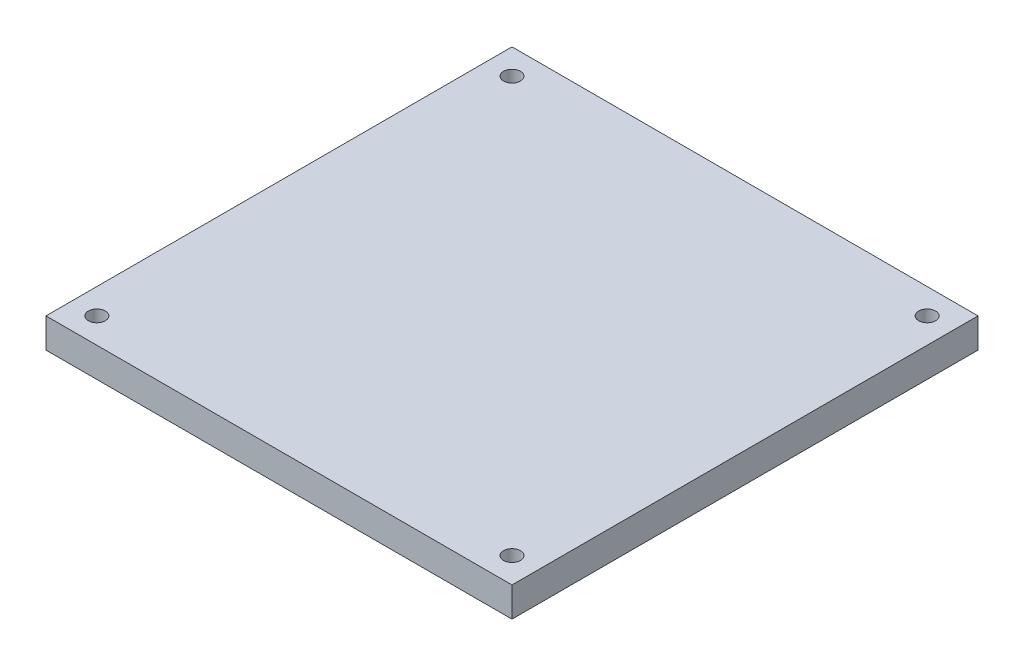
SolidWorks part; units mm, degrees
ref_plane "Plan de face" through (0, 0, 0) normal (0, 0, 1) x (1, 0, 0)
ref_plane "Plan de dessus" through (0, 0, 0) normal (0, 1, 0) x (1, 0, 0)
ref_plane "Plan de droite" through (0, 0, 0) normal (1, 0, 0) x (0, 0, -1)
sketch "Esquisse1" plane through (0, 0, 0) normal (0, 1, 0) x (1, 0, 0)
  line L0 (-26.5217, 31.7252) -> (-26.5217, -78.2748)
  line L1 (-26.5217, -78.2748) -> (83.4783, -78.2748)
  line L2 (83.4783, -78.2748) -> (83.4783, 31.7252)
  line L3 (83.4783, 31.7252) -> (-26.5217, 31.7252)
  dimension "D1" = 110
  dimension "D2" = 110
extrude "Boss.-Extru.1" add sketch "Esquisse1" along normal blind 7
sketch "Esquisse4" plane through (0, 7, 0) normal (0, 1, 0) x (1, 0, 0)
  line L0 (-26.5217, 31.7252) -> (-26.5217, -78.2748) construction
  line L1 (-26.5217, -78.2748) -> (83.4783, -78.2748) construction
  line L2 (83.4783, 31.7252) -> (-26.5217, 31.7252) construction
  line L3 (83.4783, -78.2748) -> (83.4783, 31.7252) construction
  circle A0 centre (-20.5217, -72.2748) radius 2
  circle A1 centre (-20.5217, 25.7252) radius 2
  circle A2 centre (77.4783, 25.7252) radius 2
  circle A3 centre (77.4783, -72.2748) radius 2
  dimension "D1" = 4
  dimension "D4" = 4
  dimension "D7" = 4
  dimension "D10" = 4
  dimension "D2" = 6
  dimension "D3" = 6
  dimension "D5" = 6
  dimension "D6" = 6
  dimension "D8" = 6
  dimension "D9" = 6
  dimension "D11" = 6
  dimension "D12" = 6
extrude "Enlèv. mat.-Extru.2" cut sketch "Esquisse4" against normal through all
